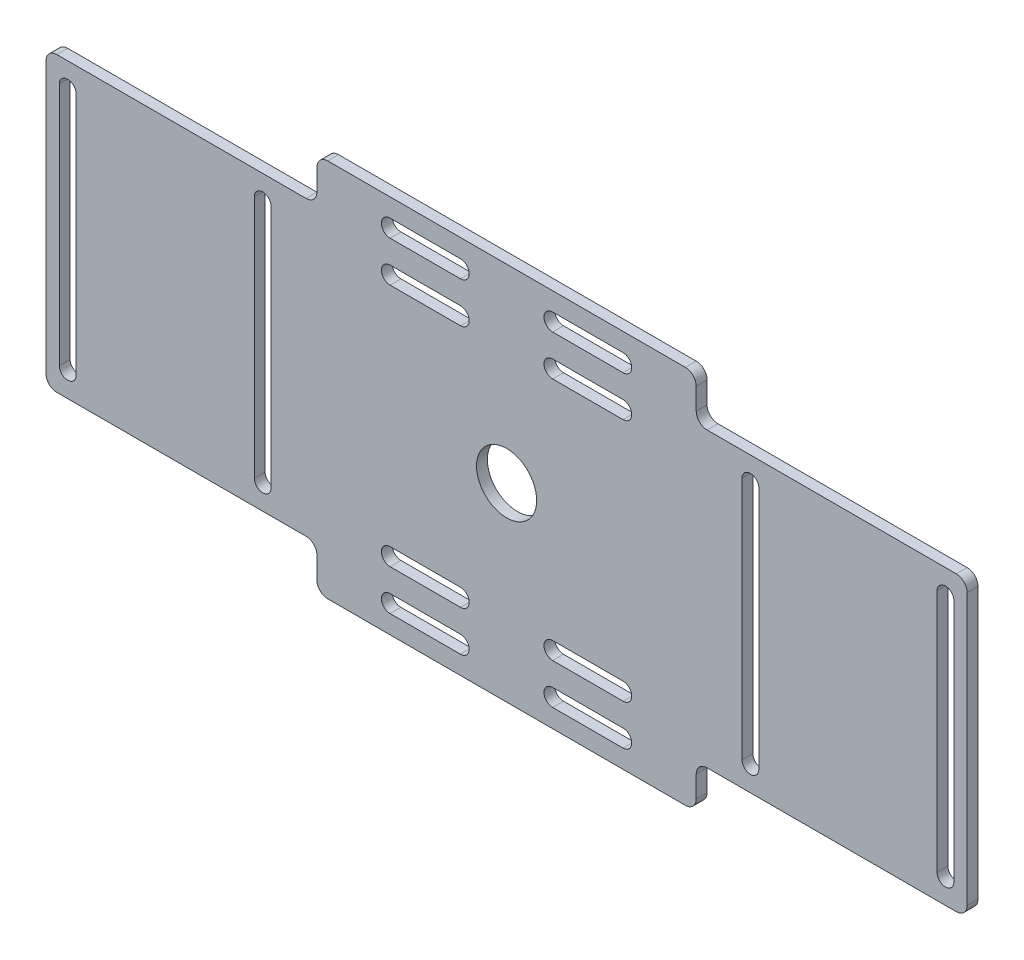
SolidWorks part; units mm, degrees
ref_plane "前基準面" through (0, 0, 0) normal (0, 0, 1) x (1, 0, 0)
ref_plane "上基準面" through (0, 0, 0) normal (0, 1, 0) x (1, 0, 0)
ref_plane "右基準面" through (0, 0, 0) normal (1, 0, 0) x (0, 0, -1)
sketch "草圖1" plane through (0, 0, 0) normal (0, 0, 1) x (1, 0, 0)
  line L1 (-85, 35) -> (85, 35)
  line L2 (-85, 35) -> (-85, -35)
  line L3 (-85, -35) -> (85, -35)
  line L4 (85, 35) -> (85, -35)
  line L5 (-85, 35) -> (85, -35) construction
  line L6 (-85, -35) -> (85, 35) construction
  point P0 (0, 0)
  dimension "D1" = 170
  dimension "D2" = 70
extrude "填料-伸長1" add sketch "草圖1" along normal blind 2
sketch "草圖2" plane through (0, 0, 2) normal (0, 0, 1) x (1, 0, 0)
  line L0 (-1000, 0) -> (49000, 0) construction
  line L1 (45, -986.1952) -> (45, 49013.8048) construction
  line L2 (-81, -962.7943) -> (-81, 49037.2057) construction
  line L3 (45, -22.5) -> (45, 22.5) construction
  line L4 (43.45, -22.5) -> (43.45, 22.5)
  line L5 (46.55, -22.5) -> (46.55, 22.5)
  line L6 (-45, -1000) -> (-45, 49000) construction
  line L7 (-45, -22.5) -> (-45, 22.5) construction
  line L8 (-46.55, -22.5) -> (-46.55, 22.5)
  line L9 (-43.45, -22.5) -> (-43.45, 22.5)
  line L10 (0, -1000) -> (0, 49000) construction
  line L11 (-1005.6924, 30) -> (48994.3076, 30) construction
  line L12 (-1002.3566, -30) -> (48997.6434, -30) construction
  line L13 (21.5, 30) -> (8.5, 30) construction
  line L16 (21.5, 28.4) -> (8.5, 28.4)
  line L19 (81, -968.4295) -> (81, 49031.5705) construction
  line L20 (-81, -22.5) -> (-81, 22.5) construction
  line L21 (-82.55, -22.5) -> (-82.55, 22.5)
  line L22 (-79.45, -22.5) -> (-79.45, 22.5)
  line L23 (81, -22.5) -> (81, 22.5) construction
  line L24 (79.45, -22.5) -> (79.45, 22.5)
  line L25 (82.55, -22.5) -> (82.55, 22.5)
  line L26 (21.5, 31.6) -> (8.5, 31.6)
  line L27 (21.5, 22.5) -> (8.5, 22.5) construction
  line L28 (21.5, 20.9) -> (8.5, 20.9)
  line L29 (21.5, 24.1) -> (8.5, 24.1)
  line L30 (-21.5, 30) -> (-8.5, 30) construction
  line L31 (-21.5, 28.4) -> (-8.5, 28.4)
  line L32 (-21.5, 31.6) -> (-8.5, 31.6)
  line L33 (-21.5, 22.5) -> (-8.5, 22.5) construction
  line L34 (-21.5, 20.9) -> (-8.5, 20.9)
  line L35 (-21.5, 24.1) -> (-8.5, 24.1)
  line L36 (21.5, -30) -> (8.5, -30) construction
  line L37 (21.5, -28.4) -> (8.5, -28.4)
  line L38 (21.5, -31.6) -> (8.5, -31.6)
  line L39 (21.5, -22.5) -> (8.5, -22.5) construction
  line L40 (21.5, -20.9) -> (8.5, -20.9)
  line L41 (21.5, -24.1) -> (8.5, -24.1)
  line L42 (-21.5, -30) -> (-8.5, -30) construction
  line L43 (-21.5, -28.4) -> (-8.5, -28.4)
  line L44 (-21.5, -31.6) -> (-8.5, -31.6)
  line L45 (-21.5, -22.5) -> (-8.5, -22.5) construction
  line L46 (-21.5, -20.9) -> (-8.5, -20.9)
  line L47 (-21.5, -24.1) -> (-8.5, -24.1)
  arc A0 (43.45, -22.5) -> (46.55, -22.5) centre (45, -22.5) ccw
  arc A1 (46.55, 22.5) -> (43.45, 22.5) centre (45, 22.5) ccw
  arc A2 (-46.55, -22.5) -> (-43.45, -22.5) centre (-45, -22.5) ccw
  arc A3 (-43.45, 22.5) -> (-46.55, 22.5) centre (-45, 22.5) ccw
  arc A12 (-82.55, -22.5) -> (-79.45, -22.5) centre (-81, -22.5) ccw
  arc A13 (-79.45, 22.5) -> (-82.55, 22.5) centre (-81, 22.5) ccw
  arc A14 (79.45, -22.5) -> (82.55, -22.5) centre (81, -22.5) ccw
  arc A15 (82.55, 22.5) -> (79.45, 22.5) centre (81, 22.5) ccw
  circle A16 centre (0, 0) radius 5.55
  arc A17 (21.5, 28.4) -> (21.5, 31.6) centre (21.5, 30) ccw
  arc A18 (8.5, 31.6) -> (8.5, 28.4) centre (8.5, 30) ccw
  arc A19 (21.5, 20.9) -> (21.5, 24.1) centre (21.5, 22.5) ccw
  arc A20 (8.5, 24.1) -> (8.5, 20.9) centre (8.5, 22.5) ccw
  arc A21 (-21.5, 28.4) -> (-21.5, 31.6) centre (-21.5, 30) cw
  arc A22 (-8.5, 31.6) -> (-8.5, 28.4) centre (-8.5, 30) cw
  arc A23 (-21.5, 20.9) -> (-21.5, 24.1) centre (-21.5, 22.5) cw
  arc A24 (-8.5, 24.1) -> (-8.5, 20.9) centre (-8.5, 22.5) cw
  arc A25 (21.5, -28.4) -> (21.5, -31.6) centre (21.5, -30) cw
  arc A26 (8.5, -31.6) -> (8.5, -28.4) centre (8.5, -30) cw
  arc A27 (21.5, -20.9) -> (21.5, -24.1) centre (21.5, -22.5) cw
  arc A28 (8.5, -24.1) -> (8.5, -20.9) centre (8.5, -22.5) cw
  arc A29 (-21.5, -28.4) -> (-21.5, -31.6) centre (-21.5, -30) ccw
  arc A30 (-8.5, -31.6) -> (-8.5, -28.4) centre (-8.5, -30) ccw
  arc A31 (-21.5, -20.9) -> (-21.5, -24.1) centre (-21.5, -22.5) ccw
  arc A32 (-8.5, -24.1) -> (-8.5, -20.9) centre (-8.5, -22.5) ccw
  point P9 (45, 0)
  point P16 (-45, 0)
  point P31 (15, 30)
  point P39 (15, 22.5)
  point P47 (-81, 0)
  point P54 (81, 0)
  point P63 (-15, 30)
  point P70 (-15, 22.5)
  point P77 (15, -30)
  point P84 (15, -22.5)
  point P91 (-15, -30)
  point P98 (-15, -22.5)
  dimension "D10" = 1.6
  dimension "D20" = 11.1
  dimension "D12" = 8.5
  dimension "D2" = 45
  dimension "D3" = 3.1
  dimension "D4" = 90
  dimension "D5" = 45
  dimension "D6" = 3.1
  dimension "D7" = 45
  dimension "D8" = 60
  dimension "D9" = 30
  dimension "D11" = 13
  dimension "D13" = 2
  dimension "D14" = 162
  dimension "D15" = 81
  dimension "D16" = 3.1
  dimension "D17" = 45
  dimension "D18" = 45
  dimension "D19" = 3.1
extrude "除料-伸長1" cut sketch "草圖2" against normal through all
sketch "草圖4" plane through (0, 0, 2) normal (0, 0, 1) x (1, 0, 0)
  line L0 (0, 52.0279) -> (0, -54.8062) construction
  line L1 (85, 35) -> (33, 35)
  line L2 (85, 35) -> (85, 25)
  line L3 (83, 27) -> (37, 27)
  line L4 (35, 33) -> (35, 29)
  line L5 (85, -35) -> (85, 35) construction
  line L6 (-98.2871, 0) -> (106.0141, 0) construction
  line L8 (35, -33) -> (35, -29)
  line L9 (83, -27) -> (37, -27)
  line L10 (85, -35) -> (85, -25)
  line L11 (85, -35) -> (33, -35)
  line L12 (-85, -35) -> (-33, -35)
  line L13 (-85, -35) -> (-85, -25)
  line L14 (-83, -27) -> (-37, -27)
  line L15 (-35, -33) -> (-35, -29)
  line L16 (-35, 33) -> (-35, 29)
  line L17 (-83, 27) -> (-37, 27)
  line L18 (-85, 35) -> (-85, 25)
  line L19 (-85, 35) -> (-33, 35)
  arc A0 (83, 27) -> (85, 25) centre (83, 25) cw
  arc A1 (37, 27) -> (35, 29) centre (37, 29) cw
  arc A2 (35, 33) -> (33, 35) centre (33, 33) ccw
  arc A3 (35, -33) -> (33, -35) centre (33, -33) cw
  arc A4 (37, -27) -> (35, -29) centre (37, -29) ccw
  arc A5 (83, -27) -> (85, -25) centre (83, -25) ccw
  arc A6 (-83, -27) -> (-85, -25) centre (-83, -25) cw
  arc A7 (-37, -27) -> (-35, -29) centre (-37, -29) cw
  arc A8 (-35, -33) -> (-33, -35) centre (-33, -33) ccw
  arc A9 (-35, 33) -> (-33, 35) centre (-33, 33) cw
  arc A10 (-37, 27) -> (-35, 29) centre (-37, 29) ccw
  arc A11 (-83, 27) -> (-85, 25) centre (-83, 25) ccw
  dimension "D1" = 2
  dimension "D2" = 2
  dimension "D3" = 2
  dimension "D4" = 52
  dimension "D5" = 8
extrude "除料-伸長2" cut sketch "草圖4" against normal through all
